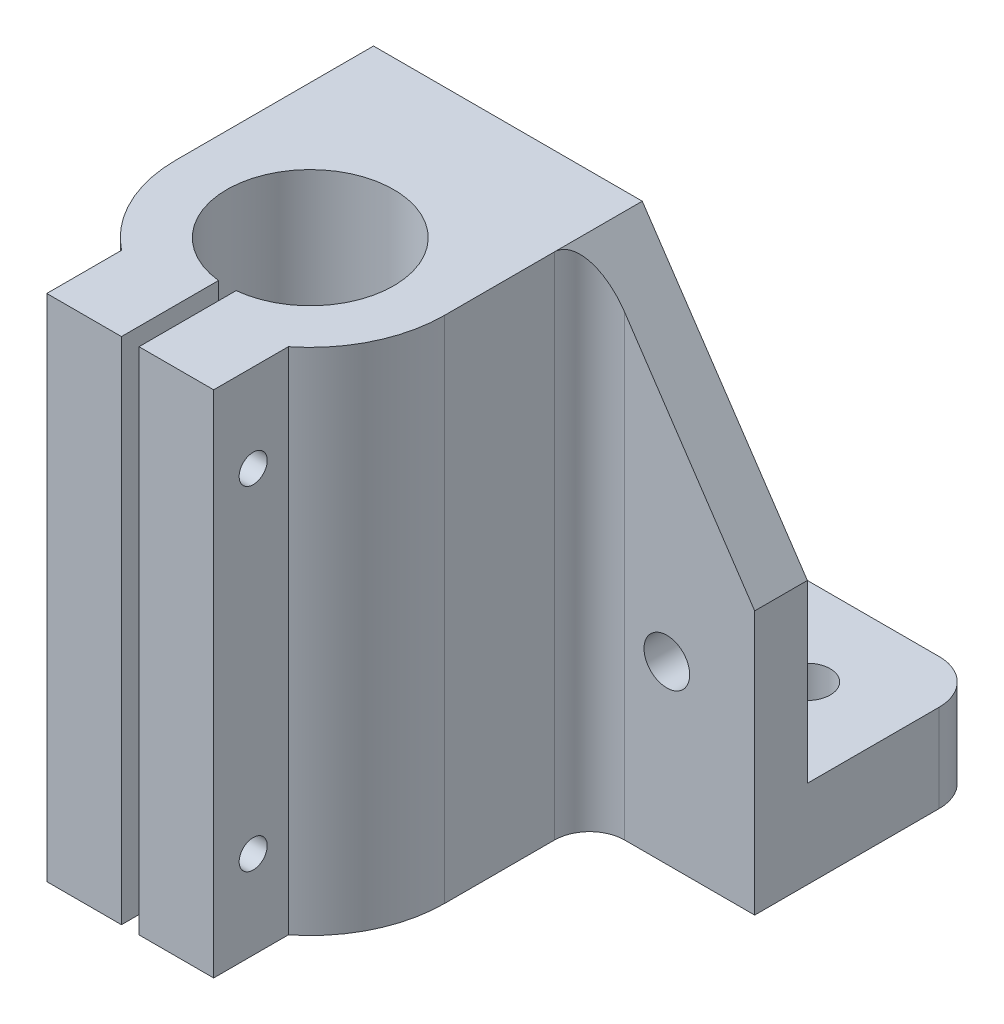
SolidWorks part; units mm, degrees
material "ABS"
ref_plane "Front Plane" through (0, 0, 0) normal (0, 0, 1) x (1, 0, 0)
ref_plane "Top Plane" through (0, 0, 0) normal (0, 1, 0) x (1, 0, 0)
ref_plane "Right Plane" through (0, 0, 0) normal (1, 0, 0) x (0, 0, -1)
sketch "Sketch1" plane through (0, 0, 0) normal (0, 1, 0) x (1, 0, 0)
  line L0 (0, 0) -> (34.1, 0)
  line L1 (34.1, 0) -> (34.1, -6)
  line L2 (34.1, -6) -> (15.3, -6)
  line L3 (15.3, -6) -> (15.3, -22.5)
  line L5 (-15.3, -22.5) -> (-15.3, -6)
  line L6 (-15.3, -6) -> (-34.1, -6)
  line L7 (-34.1, -6) -> (-34.1, 0)
  line L8 (-34.1, 0) -> (0, 0)
  line L9 (9.5, -34.4933) -> (9.5, -43)
  line L10 (9.5, -43) -> (-9.5, -43)
  line L11 (-9.5, -43) -> (-9.5, -34.4933)
  arc A0 (-15.3, -22.5) -> (-9.5, -34.4933) centre (0, -22.5) ccw
  arc A1 (9.5, -34.4933) -> (15.3, -22.5) centre (0, -22.5) ccw
  dimension "D1" = 15.3
  dimension "D2" = 19
  dimension "D3" = 6
  dimension "D4" = 16.5
  dimension "D5" = 43
  dimension "D6" = 68.2
extrude "Boss-Extrude1" add sketch "Sketch1" along normal blind 58
sketch "Sketch2" plane through (0, 58, 0) normal (0, 1, 0) x (1, 0, 0)
  line L0 (-1, -31.9472) -> (-1, -43)
  line L1 (-9.5, -43) -> (9.5, -43) construction
  line L2 (1, -43) -> (1, -31.9472)
  line L3 (-1, -43) -> (1, -43)
  arc A0 (1, -31.9472) -> (-1, -31.9472) centre (0, -22.5) ccw
  dimension "D1" = 19
  dimension "D2" = 2
extrude "Cut-Extrude1" cut sketch "Sketch2" against normal through all
sketch "Sketch3" plane through (0, 0, 0) normal (0, 0, -1) x (-1, 0, 0)
  line L0 (-34.1, 0) -> (-34.1, 10)
  line L1 (-34.1, 58) -> (-34.1, 0) construction
  line L2 (-34.1, 10) -> (34.1, 10)
  line L3 (34.1, 58) -> (34.1, 0) construction
  line L4 (34.1, 10) -> (34.1, 0)
  line L5 (34.1, 0) -> (-34.1, 0)
  dimension "D1" = 10
extrude "Boss-Extrude2" add sketch "Sketch3" along normal blind 20
sketch "Sketch4" plane through (9.5, 0, 0) normal (1, 0, 0) x (0, 0, -1)
  line L0 (-38.5, 48) -> (-38.5, 10) construction
  line L1 (-43, 58) -> (-34.4933, 58) construction
  line L2 (-43, 0) -> (-34.4933, 0) construction
  line L3 (-43, 58) -> (-43, 0) construction
  circle A0 centre (-38.5, 48) radius 1.6
  circle A1 centre (-38.5, 10) radius 1.6
  dimension "D3" = 3.2
  dimension "D1" = 10
  dimension "D2" = 10
  dimension "D4" = 4.5
extrude "Cut-Extrude2" cut sketch "Sketch4" against normal through all
sketch "Sketch5" plane through (0, 0, 0) normal (0, 0, -1) x (-1, 0, 0)
  line L0 (-34.1, 20) -> (-24.1, 20) construction
  line L1 (-34.1, 58) -> (-34.1, 10) construction
  line L2 (-24.1, 20) -> (24.1, 20) construction
  line L3 (24.1, 20) -> (34.1, 20) construction
  line L4 (34.1, 58) -> (34.1, 10) construction
  line L5 (34.1, 10) -> (-34.1, 10) construction
  circle A0 centre (-24.1, 20) radius 2.6
  circle A1 centre (24.1, 20) radius 2.6
  dimension "D3" = 5.2
  dimension "D1" = 10
  dimension "D2" = 10
extrude "Cut-Extrude3" cut sketch "Sketch5" against normal through all
sketch "Sketch6" plane through (0, 10, 0) normal (0, 1, 0) x (1, 0, 0)
  line L0 (34.1, 10) -> (24.1, 10) construction
  line L1 (34.1, 20) -> (34.1, 0) construction
  line L2 (24.1, 10) -> (-24.1, 10) construction
  line L3 (-24.1, 10) -> (-34.1, 10) construction
  line L4 (-34.1, 20) -> (-34.1, 0) construction
  circle A0 centre (24.1, 10) radius 2.6
  circle A1 centre (0, 10) radius 2.6
  circle A2 centre (-24.1, 10) radius 2.6
  dimension "D2" = 5.2
  dimension "D1" = 10
extrude "Cut-Extrude4" cut sketch "Sketch6" against normal through all
sketch "Sketch7" plane through (0, 0, 6) normal (0, 0, 1) x (1, 0, 0)
  line L0 (15.3, 58) -> (34.1, 30)
  line L1 (34.1, 58) -> (34.1, 0) construction
  line L2 (34.1, 30) -> (34.1, 58)
  line L3 (34.1, 58) -> (15.3, 58)
  line L4 (-15.3, 58) -> (-34.1, 58)
  line L5 (-34.1, 58) -> (-34.1, 30)
  line L6 (-34.1, 58) -> (-34.1, 0) construction
  line L7 (-34.1, 30) -> (-15.3, 58)
  line L8 (-34.1, 30) -> (34.1, 30) construction
  line L9 (0, 30) -> (0, 0) construction
  line L10 (-34.1, 0) -> (-15.3, 0) construction
  dimension "D1" = 30
extrude "Cut-Extrude5" cut sketch "Sketch7" against normal through all
fillet "Fillet1" radius 4 2 edges at (15.3, 29, 6) (-15.3, 29, 6)
fillet "Fillet2" radius 5 2 edges at (-34.1, 5, -20) (34.1, 5, -20)
